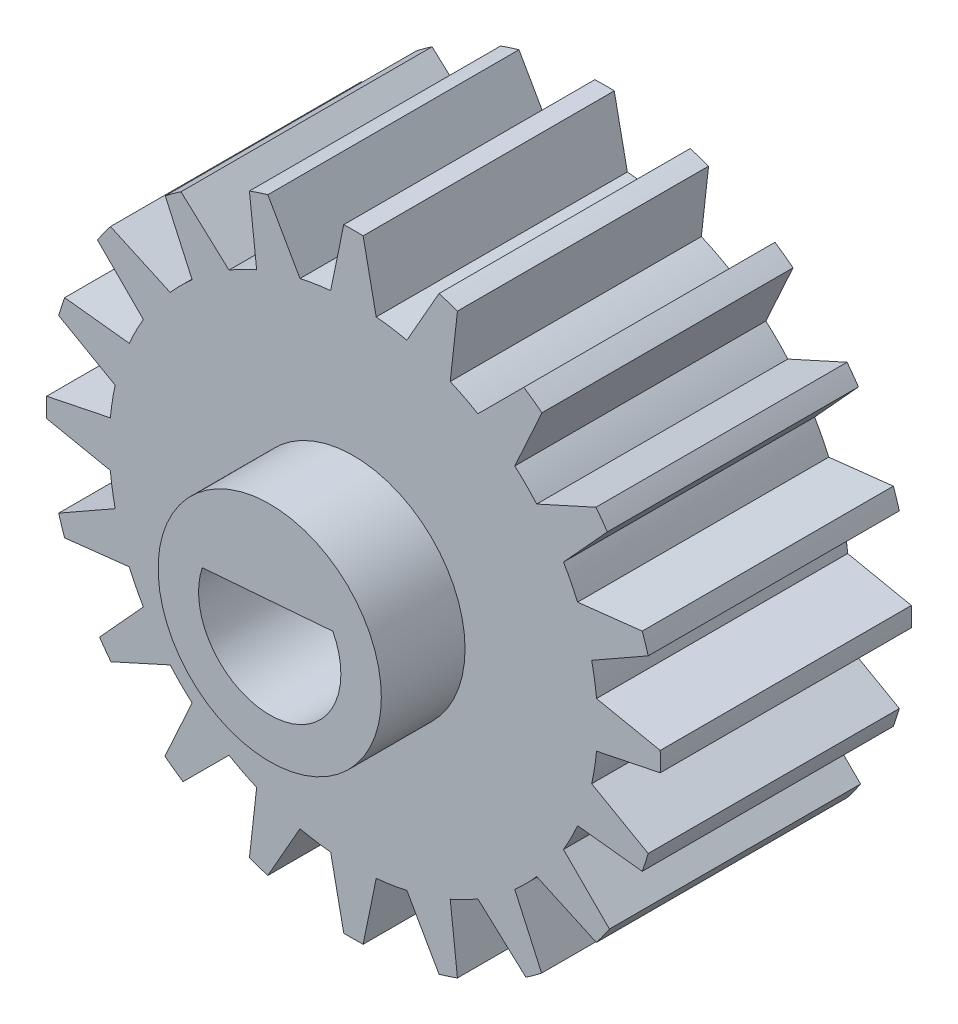
SolidWorks part; units mm, degrees
ref_plane "前视基准面" through (0, 0, 0) normal (0, 0, 1) x (1, 0, 0)
ref_plane "上视基准面" through (0, 0, 0) normal (0, 1, 0) x (1, 0, 0)
ref_plane "右视基准面" through (0, 0, 0) normal (1, 0, 0) x (0, 0, -1)
other "Configuration Table"
sketch "草图1" plane through (0, 0, 0) normal (0, 0, 1) x (1, 0, 0)
  line L0 (4.5201, 2.3619) -> (-4.8339, 1.6257)
  circle A0 centre (0, 0) radius 8
  arc A1 (-4.8339, 1.6257) -> (4.5201, 2.3619) centre (0, 0) ccw
extrude "凸台-拉伸1" add sketch "草图1" along normal blind 24
sketch "草图2" plane through (0, 0, 0) normal (0, 0, 1) x (1, 0, 0)
  circle A0 centre (0, 0) radius 17.5
  circle A1 centre (0, 0) radius 8
extrude "凸台-拉伸2" add sketch "草图2" along normal blind 18
sketch "草图3" plane through (0, 0, 0) normal (0, 0, 1) x (1, 0, 0)
  line L0 (17.4237, 1.6329) -> (21.989, 0.6948)
  line L1 (21.989, -0.6948) -> (17.4237, -1.6329)
  arc A0 (17.4237, -1.6329) -> (17.4237, 1.6329) centre (0, 0) ccw
  arc A1 (21.989, 0.6948) -> (21.989, -0.6948) centre (0, 0) cw
extrude "凸台-拉伸3" add sketch "草图3" along normal blind 18
sketch "草图4" plane through (0, 0, 0) normal (0, 0, 1) x (1, 0, 0)
  line L0 (16.0663, 6.9372) -> (20.6981, 7.4557)
  line L1 (21.1275, 6.1342) -> (17.0755, 3.8312)
  arc A0 (17.0755, 3.8312) -> (16.0663, 6.9372) centre (0, 0) ccw
  arc A1 (20.6981, 7.4557) -> (21.1275, 6.1342) centre (0, 0) cw
extrude "凸台-拉伸4" add sketch "草图4" along normal blind 18
sketch "草图5" plane through (0, 0, 0) normal (0, 0, 1) x (1, 0, 0)
  line L0 (13.1362, 11.5624) -> (17.3811, 13.4869)
  line L1 (18.1979, 12.3627) -> (15.0558, 8.9203)
  arc A0 (15.0558, 8.9203) -> (13.1362, 11.5624) centre (0, 0) ccw
  arc A1 (17.3811, 13.4869) -> (18.1979, 12.3627) centre (0, 0) cw
extrude "凸台-拉伸5" add sketch "草图5" along normal blind 18
sketch "草图6" plane through (0, 0, 0) normal (0, 0, 1) x (1, 0, 0)
  line L0 (8.9203, 15.0558) -> (12.2126, 18.3481)
  line L1 (13.5119, 17.4134) -> (11.5624, 13.1362)
  arc A0 (11.5624, 13.1362) -> (8.9203, 15.0558) centre (0, 0) ccw
  arc A1 (12.2126, 18.3481) -> (13.5119, 17.4134) centre (0, 0) cw
extrude "凸台-拉伸6" add sketch "草图6" along normal blind 18
sketch "草图7" plane through (0, 0, 0) normal (0, 0, 1) x (1, 0, 0)
  line L0 (3.8312, 17.0755) -> (6.1342, 21.1275)
  line L1 (7.4557, 20.6981) -> (6.9372, 16.0663)
  arc A0 (6.9372, 16.0663) -> (3.8312, 17.0755) centre (0, 0) ccw
  arc A1 (6.1342, 21.1275) -> (7.4557, 20.6981) centre (0, 0) cw
extrude "凸台-拉伸7" add sketch "草图7" along normal blind 18
sketch "草图8" plane through (0, 0, 0) normal (0, 0, 1) x (1, 0, 0)
  line L0 (-1.6329, 17.4237) -> (-0.6948, 21.989)
  line L1 (0.6948, 21.989) -> (1.6329, 17.4237)
  arc A0 (1.6329, 17.4237) -> (-1.6329, 17.4237) centre (0, 0) ccw
  arc A1 (-0.6948, 21.989) -> (0.6948, 21.989) centre (0, 0) cw
extrude "凸台-拉伸8" add sketch "草图8" along normal blind 18
sketch "草图9" plane through (0, 0, 0) normal (0, 0, 1) x (1, 0, 0)
  line L0 (-6.9372, 16.0663) -> (-7.4557, 20.6981)
  line L1 (-6.1342, 21.1275) -> (-3.8312, 17.0755)
  arc A0 (-3.8312, 17.0755) -> (-6.9372, 16.0663) centre (0, 0) ccw
  arc A1 (-7.4557, 20.6981) -> (-6.1342, 21.1275) centre (0, 0) cw
extrude "凸台-拉伸9" add sketch "草图9" along normal blind 18
sketch "草图10" plane through (0, 0, 0) normal (0, 0, 1) x (1, 0, 0)
  line L0 (-11.5624, 13.1362) -> (-13.4869, 17.3811)
  line L1 (-12.3627, 18.1979) -> (-8.9203, 15.0558)
  arc A0 (-8.9203, 15.0558) -> (-11.5624, 13.1362) centre (0, 0) ccw
  arc A1 (-13.4869, 17.3811) -> (-12.3627, 18.1979) centre (0, 0) cw
extrude "凸台-拉伸10" add sketch "草图10" along normal blind 18
sketch "草图11" plane through (0, 0, 0) normal (0, 0, 1) x (1, 0, 0)
  line L0 (-15.0558, 8.9203) -> (-18.3481, 12.2126)
  line L1 (-17.4134, 13.5119) -> (-13.1362, 11.5624)
  arc A0 (-13.1362, 11.5624) -> (-15.0558, 8.9203) centre (0, 0) ccw
  arc A1 (-18.3481, 12.2126) -> (-17.4134, 13.5119) centre (0, 0) cw
extrude "凸台-拉伸11" add sketch "草图11" along normal blind 18
sketch "草图12" plane through (0, 0, 0) normal (0, 0, 1) x (1, 0, 0)
  line L0 (-17.0755, 3.8312) -> (-21.1275, 6.1342)
  line L1 (-20.6981, 7.4557) -> (-16.0663, 6.9372)
  arc A0 (-16.0663, 6.9372) -> (-17.0755, 3.8312) centre (0, 0) ccw
  arc A1 (-21.1275, 6.1342) -> (-20.6981, 7.4557) centre (0, 0) cw
extrude "凸台-拉伸12" add sketch "草图12" along normal blind 18
sketch "草图13" plane through (0, 0, 0) normal (0, 0, 1) x (1, 0, 0)
  line L0 (-17.4237, -1.6329) -> (-21.989, -0.6948)
  line L1 (-21.989, 0.6948) -> (-17.4237, 1.6329)
  arc A0 (-17.4237, 1.6329) -> (-17.4237, -1.6329) centre (0, 0) ccw
  arc A1 (-21.989, -0.6948) -> (-21.989, 0.6948) centre (0, 0) cw
extrude "凸台-拉伸13" add sketch "草图13" along normal blind 18
sketch "草图14" plane through (0, 0, 0) normal (0, 0, 1) x (1, 0, 0)
  line L0 (-16.0663, -6.9372) -> (-20.6981, -7.4557)
  line L1 (-21.1275, -6.1342) -> (-17.0755, -3.8312)
  arc A0 (-17.0755, -3.8312) -> (-16.0663, -6.9372) centre (0, 0) ccw
  arc A1 (-20.6981, -7.4557) -> (-21.1275, -6.1342) centre (0, 0) cw
extrude "凸台-拉伸14" add sketch "草图14" along normal blind 18
sketch "草图15" plane through (0, 0, 0) normal (0, 0, 1) x (1, 0, 0)
  line L0 (-13.1362, -11.5624) -> (-17.3811, -13.4869)
  line L1 (-18.1979, -12.3627) -> (-15.0558, -8.9203)
  arc A0 (-15.0558, -8.9203) -> (-13.1362, -11.5624) centre (0, 0) ccw
  arc A1 (-17.3811, -13.4869) -> (-18.1979, -12.3627) centre (0, 0) cw
extrude "凸台-拉伸15" add sketch "草图15" along normal blind 18
sketch "草图16" plane through (0, 0, 0) normal (0, 0, 1) x (1, 0, 0)
  line L0 (-8.9203, -15.0558) -> (-12.2126, -18.3481)
  line L1 (-13.5119, -17.4134) -> (-11.5624, -13.1362)
  arc A0 (-11.5624, -13.1362) -> (-8.9203, -15.0558) centre (0, 0) ccw
  arc A1 (-12.2126, -18.3481) -> (-13.5119, -17.4134) centre (0, 0) cw
extrude "凸台-拉伸16" add sketch "草图16" along normal blind 18
sketch "草图17" plane through (0, 0, 0) normal (0, 0, 1) x (1, 0, 0)
  line L0 (-3.8312, -17.0755) -> (-6.1342, -21.1275)
  line L1 (-7.4557, -20.6981) -> (-6.9372, -16.0663)
  arc A0 (-6.9372, -16.0663) -> (-3.8312, -17.0755) centre (0, 0) ccw
  arc A1 (-6.1342, -21.1275) -> (-7.4557, -20.6981) centre (0, 0) cw
extrude "凸台-拉伸17" add sketch "草图17" along normal blind 18
sketch "草图18" plane through (0, 0, 0) normal (0, 0, 1) x (1, 0, 0)
  line L0 (1.6329, -17.4237) -> (0.6948, -21.989)
  line L1 (-0.6948, -21.989) -> (-1.6329, -17.4237)
  arc A0 (-1.6329, -17.4237) -> (1.6329, -17.4237) centre (0, 0) ccw
  arc A1 (0.6948, -21.989) -> (-0.6948, -21.989) centre (0, 0) cw
extrude "凸台-拉伸18" add sketch "草图18" along normal blind 18
sketch "草图19" plane through (0, 0, 0) normal (0, 0, 1) x (1, 0, 0)
  line L0 (6.9372, -16.0663) -> (7.4557, -20.6981)
  line L1 (6.1342, -21.1275) -> (3.8312, -17.0755)
  arc A0 (3.8312, -17.0755) -> (6.9372, -16.0663) centre (0, 0) ccw
  arc A1 (7.4557, -20.6981) -> (6.1342, -21.1275) centre (0, 0) cw
extrude "凸台-拉伸19" add sketch "草图19" along normal blind 18
sketch "草图20" plane through (0, 0, 0) normal (0, 0, 1) x (1, 0, 0)
  line L0 (11.5624, -13.1362) -> (13.4869, -17.3811)
  line L1 (12.3627, -18.1979) -> (8.9203, -15.0558)
  arc A0 (8.9203, -15.0558) -> (11.5624, -13.1362) centre (0, 0) ccw
  arc A1 (13.4869, -17.3811) -> (12.3627, -18.1979) centre (0, 0) cw
extrude "凸台-拉伸20" add sketch "草图20" along normal blind 18
sketch "草图21" plane through (0, 0, 0) normal (0, 0, 1) x (1, 0, 0)
  line L0 (15.0558, -8.9203) -> (18.3481, -12.2126)
  line L1 (17.4134, -13.5119) -> (13.1362, -11.5624)
  arc A0 (13.1362, -11.5624) -> (15.0558, -8.9203) centre (0, 0) ccw
  arc A1 (18.3481, -12.2126) -> (17.4134, -13.5119) centre (0, 0) cw
extrude "凸台-拉伸21" add sketch "草图21" along normal blind 18
sketch "草图22" plane through (0, 0, 0) normal (0, 0, 1) x (1, 0, 0)
  line L0 (17.0755, -3.8312) -> (21.1275, -6.1342)
  line L1 (20.6981, -7.4557) -> (16.0663, -6.9372)
  arc A0 (16.0663, -6.9372) -> (17.0755, -3.8312) centre (0, 0) ccw
  arc A1 (21.1275, -6.1342) -> (20.6981, -7.4557) centre (0, 0) cw
extrude "凸台-拉伸22" add sketch "草图22" along normal blind 18
